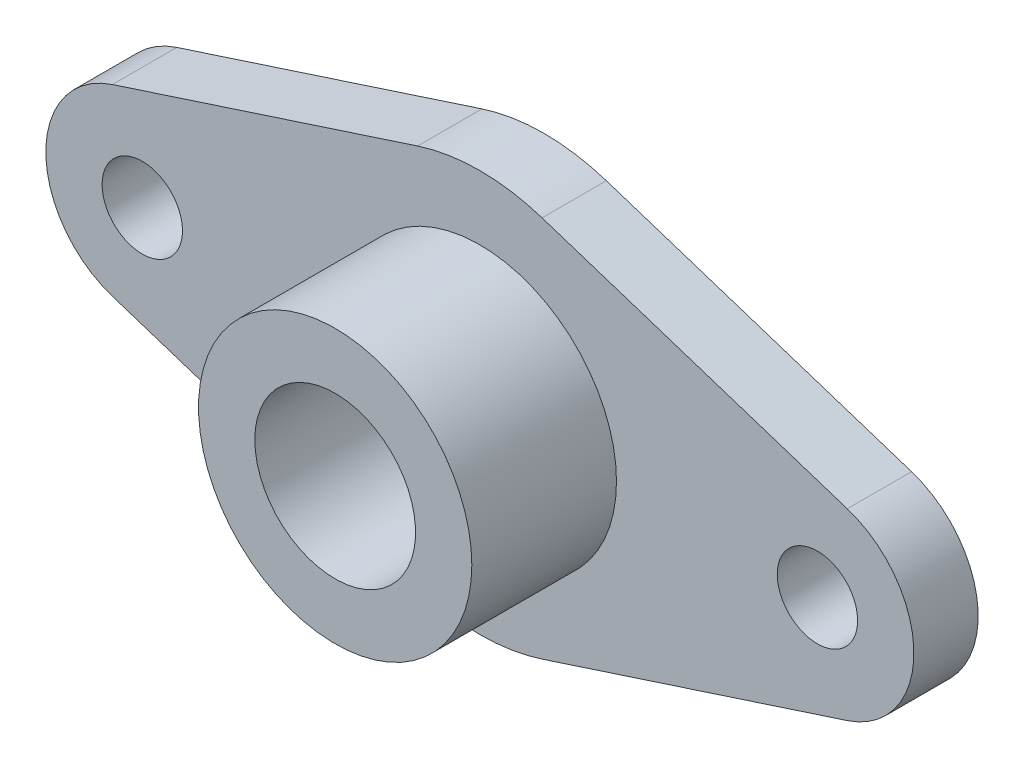
SolidWorks part; units mm, degrees
ref_plane "前视基准面" through (0, 0, 0) normal (0, 0, 1) x (1, 0, 0)
ref_plane "上视基准面" through (0, 0, 0) normal (0, 1, 0) x (1, 0, 0)
ref_plane "右视基准面" through (0, 0, 0) normal (1, 0, 0) x (0, 0, -1)
sketch "草图1" plane through (0, 0, 0) normal (0, 0, 1) x (1, 0, 0)
  line L0 (-7.7381, 23.7723) -> (-45.7143, 11.4107)
  line L1 (-45.7143, -11.4107) -> (-7.7381, -23.7723)
  line L2 (7.7381, -23.7723) -> (45.7143, -11.4107)
  line L3 (45.7143, 11.4107) -> (7.7381, 23.7723)
  arc A0 (7.7381, 23.7723) -> (-7.7381, 23.7723) centre (0, -0.0001) ccw
  arc A1 (-45.7143, 11.4107) -> (-45.7143, -11.4107) centre (-42, 0) ccw
  arc A2 (-7.7381, -23.7723) -> (7.7381, -23.7723) centre (0, 0.0001) ccw
  arc A3 (45.7143, -11.4107) -> (45.7143, 11.4107) centre (42, 0) ccw
extrude "凸台-拉伸1" add sketch "草图1" along normal blind 8
ref_plane "基准面1" through (0, 0, 8) normal (0, 0, 1) x (1, 0, 0)
sketch "草图2" plane through (0, 0, 8) normal (0, 0, 1) x (1, 0, 0)
  circle A0 centre (0, 0) radius 17
extrude "凸台-拉伸2" add sketch "草图2" along normal blind 18
sketch "草图3" plane through (0, 0, 0) normal (0, 0, 1) x (1, 0, 0)
  circle A0 centre (0, 0) radius 10
extrude "切除-拉伸1" cut sketch "草图3" along normal through all
sketch "草图4" plane through (0, 0, 0) normal (0, 0, 1) x (1, 0, 0)
  circle A0 centre (42, 0) radius 5
  circle A1 centre (-42, 0) radius 5
extrude "切除-拉伸2" cut sketch "草图4" along normal through all
